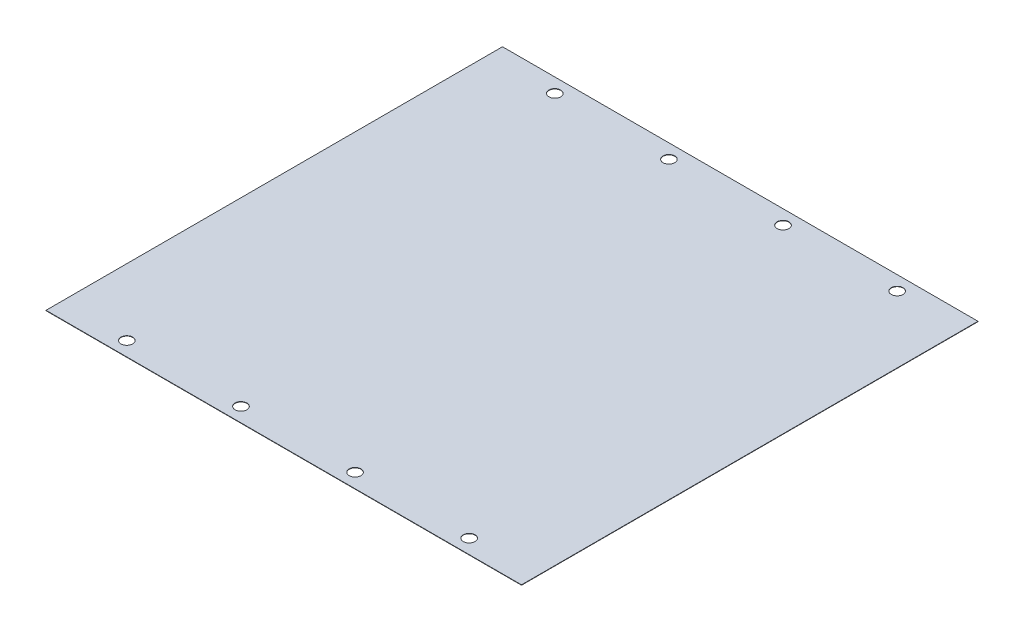
SolidWorks part; units mm, degrees
material "1023 Листовая углеродистая сталь (SS)"
ref_plane "Спереди" through (0, 0, 0) normal (0, 0, 1) x (1, 0, 0)
ref_plane "Сверху" through (0, 0, 0) normal (0, 1, 0) x (1, 0, 0)
ref_plane "Справа" through (0, 0, 0) normal (1, 0, 0) x (0, 0, -1)
sketch "Эскиз1" plane through (0, 0, 0) normal (0, 1, 0) x (1, 0, 0)
  line L0 (-90, 112.5) -> (-30, 112.5) construction
  line L1 (-125, 120) -> (125, 120)
  line L2 (-125, 120) -> (-125, -120)
  line L3 (-125, -120) -> (125, -120)
  line L4 (125, 120) -> (125, -120)
  line L5 (-30, 112.5) -> (30, 112.5) construction
  line L6 (30, 112.5) -> (90, 112.5) construction
  circle A0 centre (-90, 112.5) radius 3.1
  circle A1 centre (-30, 112.5) radius 3.1
  circle A2 centre (30, 112.5) radius 3.1
  circle A3 centre (90, 112.5) radius 3.1
  circle A4 centre (90, -112.5) radius 3.1
  circle A5 centre (30, -112.5) radius 3.1
  circle A6 centre (-30, -112.5) radius 3.1
  circle A7 centre (-90, -112.5) radius 3.1
  point P0 (0, 0)
  point P6 (0, 120)
  point P7 (125, 0)
  point P24 (0, 112.5)
  point P25 (-27.9768, 102.6891)
  point P26 (-24.9771, -100.0926)
  point P27 (0, 0)
  dimension "D3" = 6.2
  dimension "D1" = 240
  dimension "D2" = 250
  dimension "D4" = 180
  dimension "D5" = 7.5
  dimension "D6" = 7.5
extrude "База" add sketch "Эскиз1" along normal blind 0.2
